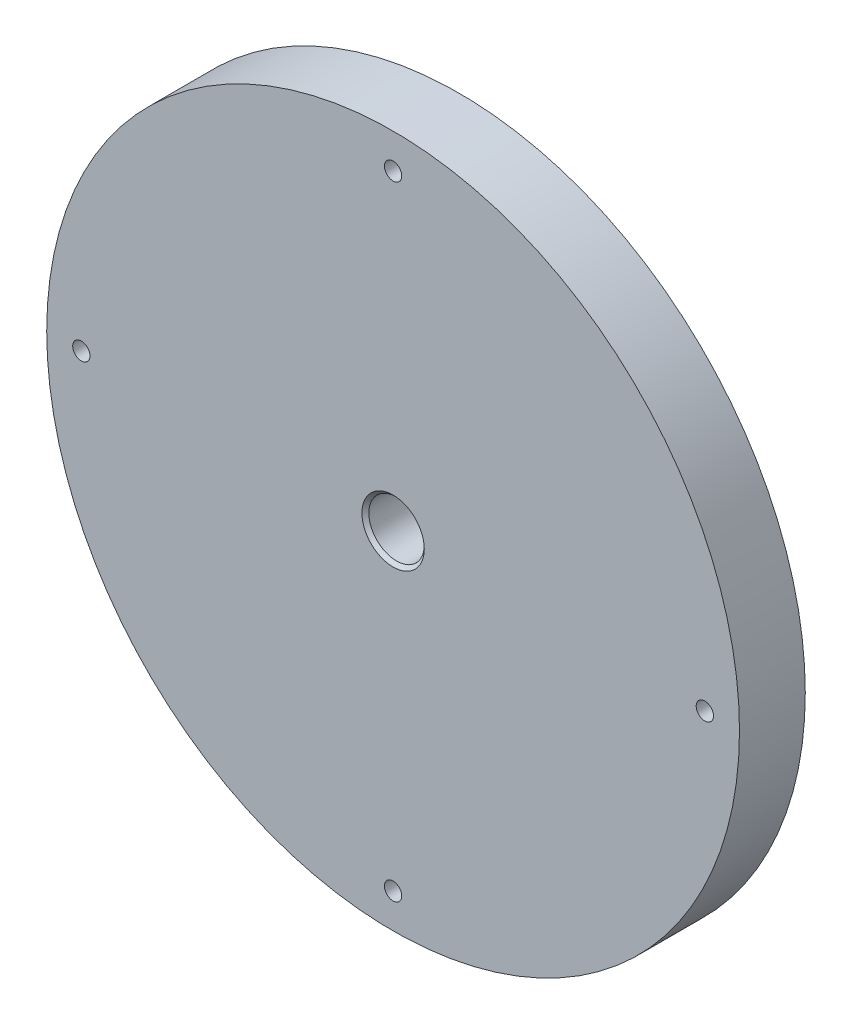
SolidWorks part; units mm, degrees
ref_plane "正面" through (0, 0, 0) normal (0, 0, 1) x (1, 0, 0)
ref_plane "平面" through (0, 0, 0) normal (0, 1, 0) x (1, 0, 0)
ref_plane "右側面" through (0, 0, 0) normal (1, 0, 0) x (0, 0, -1)
sketch "ｽｹｯﾁ1" plane through (0, 0, 0) normal (0, 0, 1) x (1, 0, 0)
  circle A0 centre (0, 0) radius 100
  dimension "D1" = 200
extrude "ﾎﾞｽ - 押し出し1" add sketch "ｽｹｯﾁ1" along normal blind 19
sketch "ｽｹｯﾁ2" plane through (0, 0, 19) normal (0, 0, 1) x (1, 0, 0)
  circle A0 centre (0, 0) radius 8
  dimension "D1" = 16
sketch "ｽｹｯﾁ6" plane through (0, 0, 19) normal (0, 0, 1) x (1, 0, 0)
  line L0 (0, 0) -> (90, 0) construction
  line L1 (0, 0) -> (0, 90) construction
  line L2 (0, 90) -> (0, 0) construction
  line L3 (0, 0) -> (-90, 0) construction
  line L4 (-90, 0) -> (0, 0) construction
  line L5 (0, 0) -> (0, -90) construction
  dimension "D1" = 90
  dimension "D2" = 90
  dimension "D3" = 90
  dimension "D4" = 90
hole_wizard "M6x1.0 ねじ穴1" positions "3Dｽｹｯﾁ1" profile "ｽｹｯﾁ7" tap size "M6x1.0" standard "JIS"
sketch3d "3Dｽｹｯﾁ1"
  point P0 (0, 90, 19)
  point P3 (-90, 0, 19)
  point P6 (0, -90, 19)
  point P9 (90, 0, 19)
sketch "ｽｹｯﾁ7" plane through (0, 90, 19) normal (1, 0, 0) x (0, -1, 0)
  line L0 (0, 0) -> (0, 18.5022)
  line L1 (0, 18.5022) -> (2.5, 17)
  line L2 (2.5, 17) -> (2.5, 0)
  line L5 (2.5, 0) -> (0, 0)
  line L10 (0, 18.5022) -> (-2.5, 17) construction
  line L11 (0, -6.35) -> (0, 107.95) construction
  dimension "ねじ下穴ﾄﾞﾘﾙ直径" = 5
  dimension "ねじ下穴ﾄﾞﾘﾙの深さ" = 17
  dimension "ﾄﾞﾘﾙ角度" = 118
extrude "ｶｯﾄ - 押し出し1" cut sketch "ｽｹｯﾁ2" against normal through all
chamfer "面取り1" distance 1 angle 45 1 edges at (8, 0, 19)
chamfer "面取り2" distance 1 angle 45 1 edges at (8, 0, 0)
